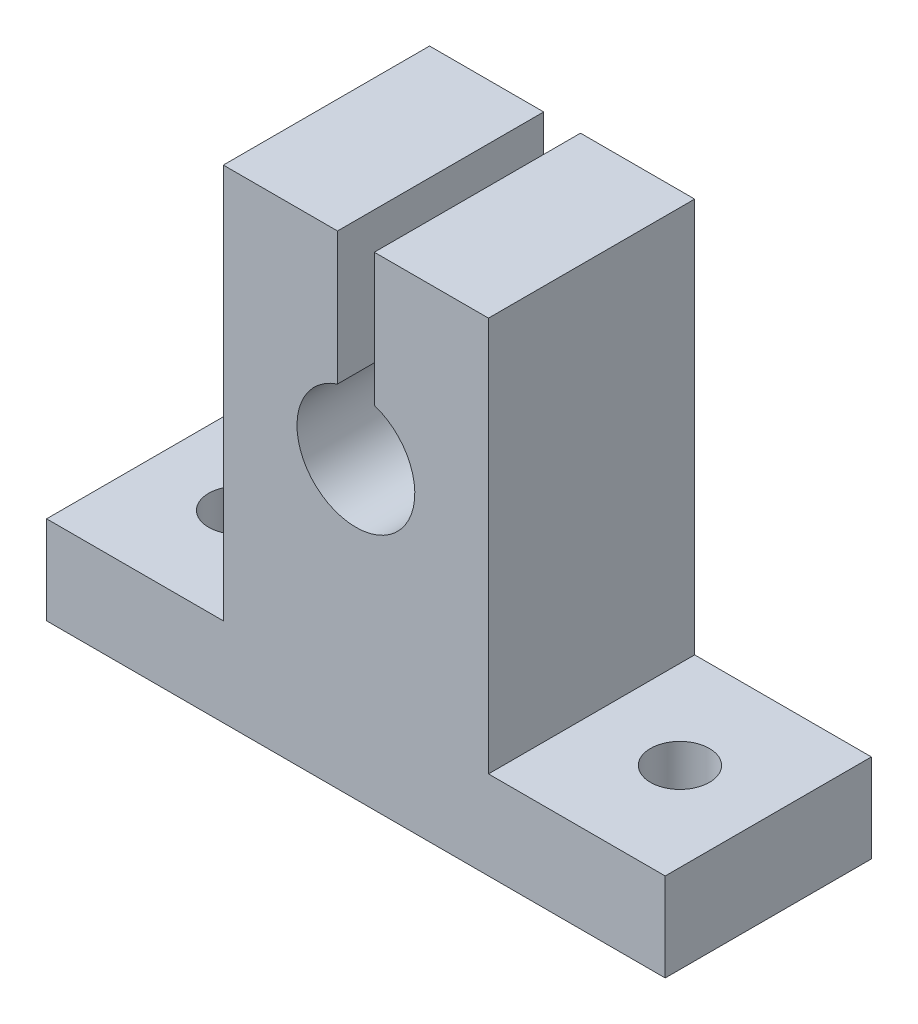
SolidWorks part; units mm, degrees
material "Alumine"
ref_plane "Front Plane" through (0, 0, 0) normal (0, 0, 1) x (1, 0, 0)
ref_plane "Top Plane" through (0, 0, 0) normal (0, 1, 0) x (1, 0, 0)
ref_plane "Right Plane" through (0, 0, 0) normal (1, 0, 0) x (0, 0, -1)
sketch "Sketch1" plane through (0, 0, 0) normal (0, 0, 1) x (1, 0, 0)
  line L0 (0, 0) -> (42, 0)
  line L1 (42, 0) -> (42, 6)
  line L2 (42, 6) -> (30, 6)
  line L3 (30, 6) -> (30, 32.8)
  line L4 (30, 32.8) -> (22.249, 32.8)
  line L7 (19.751, 32.8) -> (12, 32.8)
  line L8 (12, 32.8) -> (12, 6)
  line L9 (12, 6) -> (0, 6)
  line L10 (0, 6) -> (0, 0)
  line L11 (22.249, 32.8) -> (22.249, 23.8)
  line L12 (19.751, 32.8) -> (19.751, 23.8)
  arc A0 (19.751, 23.8) -> (22.249, 23.8) centre (21, 20) ccw
  dimension "D2" = 42
  dimension "D3" = 6
  dimension "D1" = 32.8
  dimension "D5" = 20
  dimension "D6" = 4
  dimension "D7" = 21
  dimension "D8" = 21
  dimension "D4" = 18
  dimension "D9" = 9
extrude "Boss-Extrude1" add sketch "Sketch1" along normal blind 14
sketch "Sketch2" plane through (0, 6, 0) normal (0, 1, 0) x (1, 0, 0)
  line L1 (12, 0) -> (0, 0) construction
  line L2 (0, -14) -> (0, 0) construction
  line L3 (42, -14) -> (42, 0) construction
  circle A0 centre (6, -7) radius 2
  circle A1 centre (36, -7) radius 2
  dimension "D1" = 4
  dimension "D2" = 7
  dimension "D4" = 6
  dimension "D3" = 6
extrude "Cut-Extrude1" cut sketch "Sketch2" against normal through all
